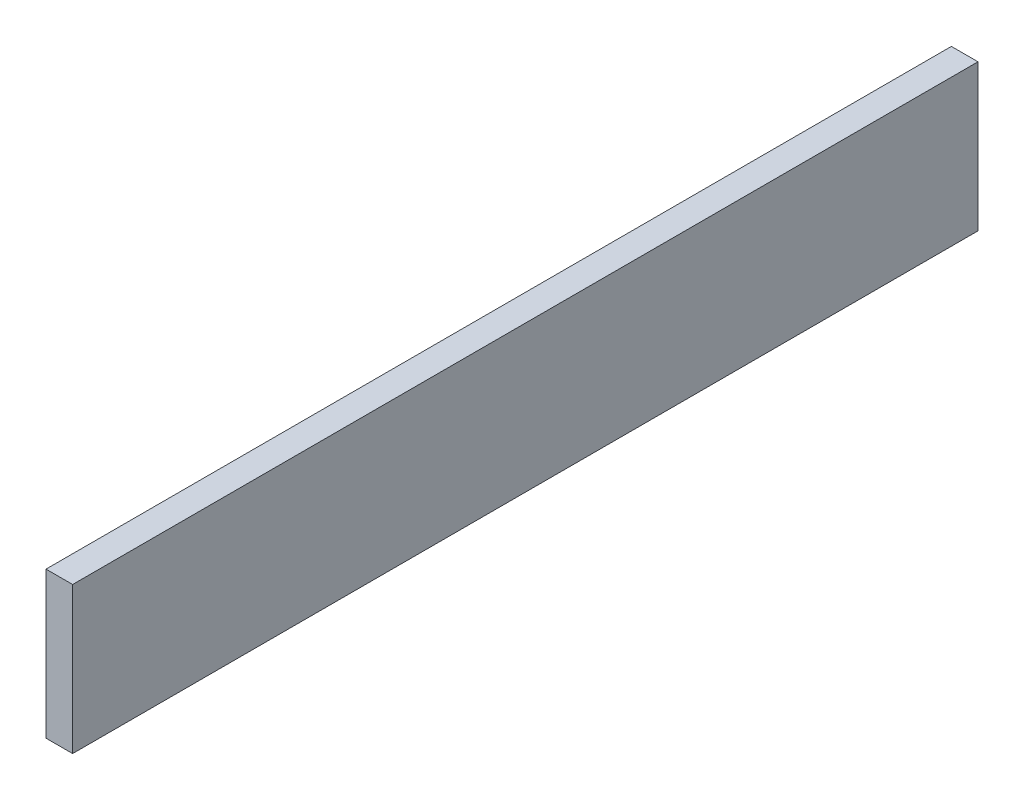
SolidWorks part; units mm, degrees
ref_plane "Front Plane" through (0, 0, 0) normal (0, 0, 1) x (1, 0, 0)
ref_plane "Top Plane" through (0, 0, 0) normal (0, 1, 0) x (1, 0, 0)
ref_plane "Right Plane" through (0, 0, 0) normal (1, 0, 0) x (0, 0, -1)
sketch "Sketch1" plane through (0, 0, 0) normal (1, 0, 0) x (0, 0, -1)
  line L1 (215.9, 34.925) -> (-215.9, 34.925)
  line L2 (215.9, 34.925) -> (215.9, -34.925)
  line L3 (215.9, -34.925) -> (-215.9, -34.925)
  line L4 (-215.9, 34.925) -> (-215.9, -34.925)
  line L5 (215.9, 34.925) -> (-215.9, -34.925) construction
  line L6 (215.9, -34.925) -> (-215.9, 34.925) construction
  point P0 (0, 0)
  dimension "D1" = 69.85
  dimension "D2" = 431.8
extrude "Boss-Extrude1" add sketch "Sketch1" along normal blind 12.7 contours L1 L4 L3 L2
